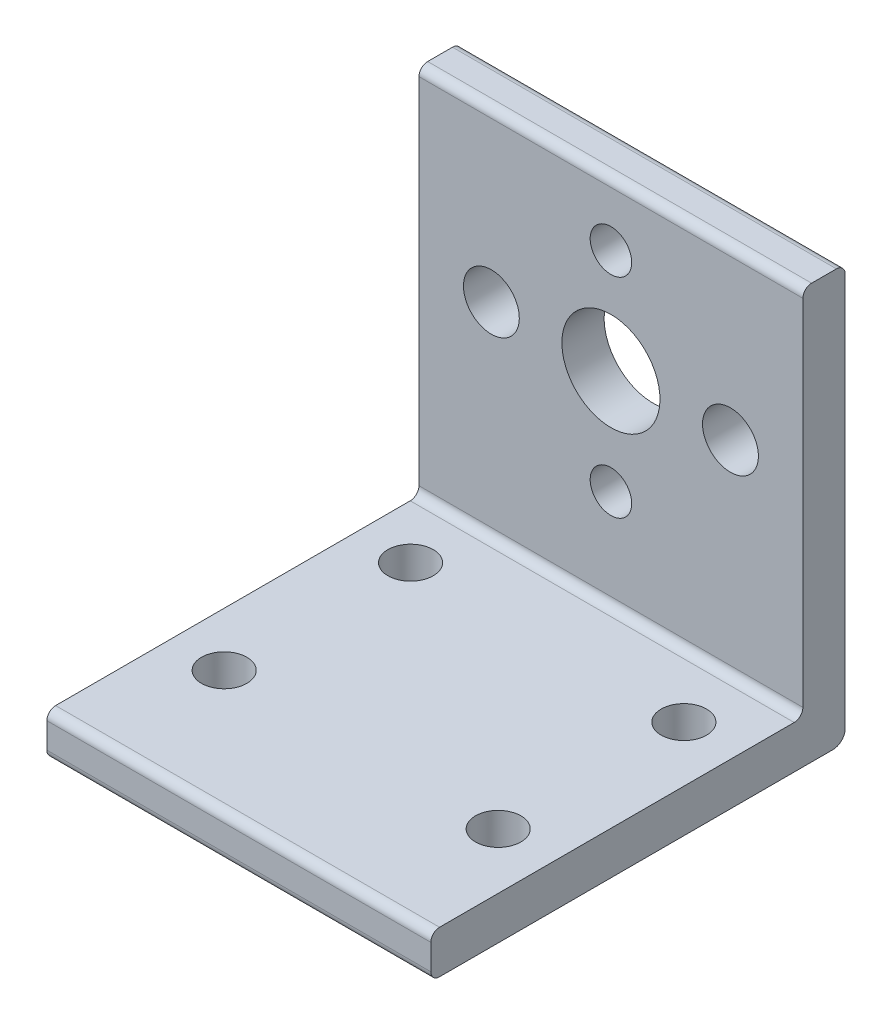
SolidWorks part; units mm, degrees
material "6061-T6 (SS)"
ref_plane "Front Plane" through (0, 0, 0) normal (0, 0, 1) x (1, 0, 0)
ref_plane "Top Plane" through (0, 0, 0) normal (0, 1, 0) x (1, 0, 0)
ref_plane "Right Plane" through (0, 0, 0) normal (1, 0, 0) x (0, 0, -1)
sketch "Sketch1" plane through (0, 0, 0) normal (1, 0, 0) x (0, 0, -1)
  line L0 (0, 0) -> (0, -30.1752)
  line L1 (0, -30.1752) -> (-30.1498, -30.1752)
  line L2 (-30.1498, -30.1752) -> (-30.1498, -27.051)
  line L3 (-30.1498, -27.051) -> (-3.0734, -27.051)
  line L4 (-3.0734, -27.051) -> (-3.0734, 0)
  line L5 (-3.0734, 0) -> (0, 0)
  dimension "D1" = 30.1498
  dimension "D2" = 30.1752
  dimension "D3" = 3.0734
  dimension "D4" = 3.1242
extrude "Boss-Extrude1" add sketch "Sketch1" along normal blind 27.94
sketch "Sketch2" plane through (0, 0, 0) normal (0, 0, 1) x (1, 0, 0)
  line L0 (13.97, -4.6101) -> (13.97, -19.7993) construction
  line L1 (27.94, -30.1752) -> (0, -30.1752) construction
  line L2 (27.94, 0) -> (0, 0) construction
  line L3 (5.2705, -12.2047) -> (22.6695, -12.2047) construction
  line L4 (27.94, -27.051) -> (0, -27.051) construction
  line L6 (0, -12.2047) -> (27.94, -12.2047) construction
  line L9 (0, 0) -> (0, -27.051) construction
  line L10 (27.94, 0) -> (27.94, -27.051) construction
  circle A0 centre (13.97, -12.2047) radius 3.5687
  circle A1 centre (13.97, -4.6101) radius 1.5113
  circle A2 centre (5.2705, -12.2047) radius 2.032
  circle A3 centre (22.6695, -12.2047) radius 2.032
  circle A4 centre (13.97, -19.7993) radius 1.5113
  point P0 (13.97, -12.2047)
  dimension "D1" = 7.1374
  dimension "D2" = 3.0226
  dimension "D3" = 12.2047
  dimension "D7" = 4.064
  dimension "D8" = 27.94
  dimension "D4" = 17.399
  dimension "D5" = 15.1892
  dimension "D6" = 30.1752
  dimension "D9" = 3.1242
extrude "Motor_Mount_holes" cut sketch "Sketch2" along normal through all
sketch "Sketch3" plane through (0, -30.1752, 0) normal (0, 1, 0) x (1, 0, 0)
  line L0 (13.97, -3.0734) -> (13.97, -30.1498) construction
  line L1 (27.94, -3.0734) -> (0, -3.0734) construction
  line L2 (27.94, -30.1498) -> (0, -30.1498) construction
  line L3 (27.94, 0) -> (0, 0) construction
  line L4 (27.94, -30.1498) -> (27.94, 0) construction
  line L5 (0, -14.5669) -> (28.2702, -14.5669) construction
  line L6 (27.94, 0) -> (0, 0) construction
  line L7 (27.94, -3.0734) -> (0, -3.0734) construction
  line L8 (0, -3.0734) -> (0, -30.1498) construction
  line L9 (27.94, -3.0734) -> (27.94, -30.1498) construction
  circle A4 centre (3.9116, -7.5946) radius 1.651
  circle A5 centre (23.9014, -7.6962) radius 1.651
  circle A6 centre (3.9116, -21.1582) radius 1.651
  circle A7 centre (23.876, -21.1836) radius 1.651
  dimension "D1" = 3.302
  dimension "D2" = 7.6962
  dimension "D3" = 4.0386
  dimension "D4" = 21.1836
  dimension "D5" = 4.064
  dimension "D6" = 7.5946
  dimension "D7" = 24.0284
  dimension "D8" = 21.1582
  dimension "D9" = 24.0284
  dimension "D10" = 3.0734
  dimension "D11" = 27.94
  dimension "D12" = 30.1498
extrude "Plate_Mount_Holes" cut sketch "Sketch3" along normal through all
fillet "Fillet1" radius 0.635 1 edges at (13.97, -27.051, 3.0734)
fillet "Fillet2" radius 0.889 1 edges at (13.97, -30.1752, 0)
fillet "Fillet3" radius 0.635 4 edges at (13.97, -30.1752, 30.1498) (13.97, -27.051, 30.1498) (13.97, 0, 0) (13.97, 0, 3.0734)
